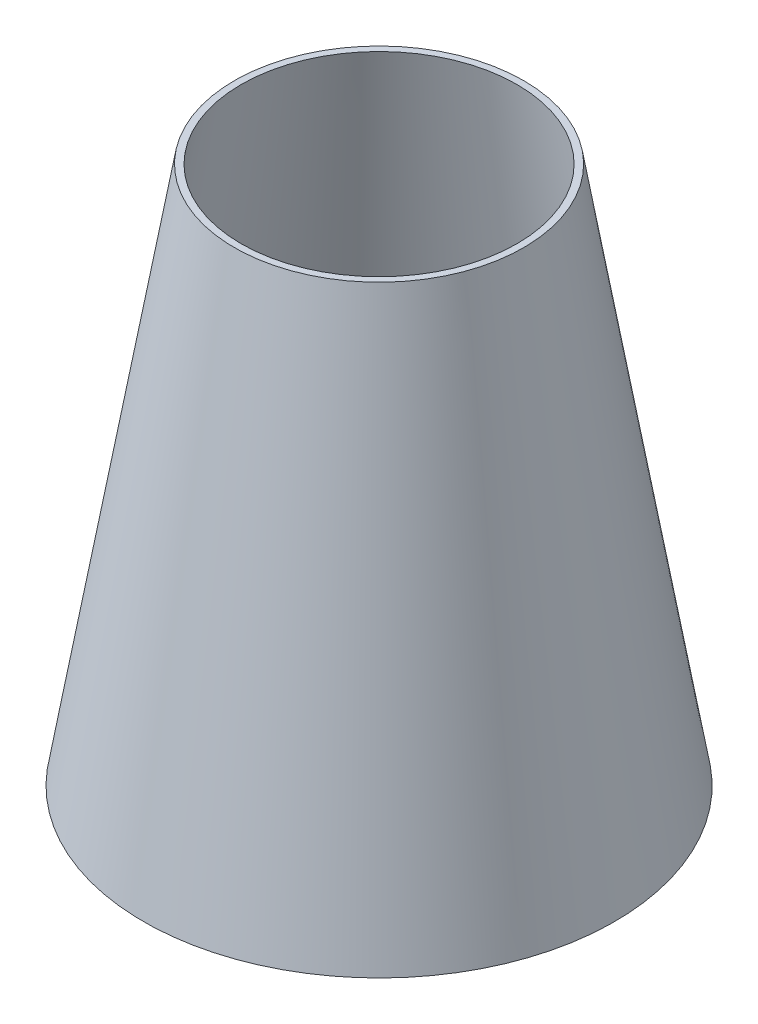
SolidWorks part; units mm, degrees
material "Fibra de Vidro A"
ref_plane "Plano frontal" through (0, 0, 0) normal (0, 0, 1) x (1, 0, 0)
ref_plane "Plano superior" through (0, 0, 0) normal (0, 1, 0) x (1, 0, 0)
ref_plane "Plano direito" through (0, 0, 0) normal (1, 0, 0) x (0, 0, -1)
other "Centro da massa"
sketch "Esboço1" plane through (0, 0, 0) normal (0, 0, 1) x (1, 0, 0)
  line L0 (0, 0) -> (-35, 0)
  line L1 (-35, 0) -> (-21.5, 80)
  line L2 (-21.5, 80) -> (-20.5, 80)
  line L3 (-20.5, 80) -> (-34, 0)
  line L4 (-34, 0) -> (-35, 0)
  line L5 (0, 0) -> (0, 48.7106) construction
  point P3 (-34, 0)
  dimension "D1" = 35
  dimension "D2" = 1
  dimension "D3" = 1
  dimension "D4" = 20.5
  dimension "D5" = 80
revolve "Revolução1" add sketch "Esboço1" angle 360 about L5
